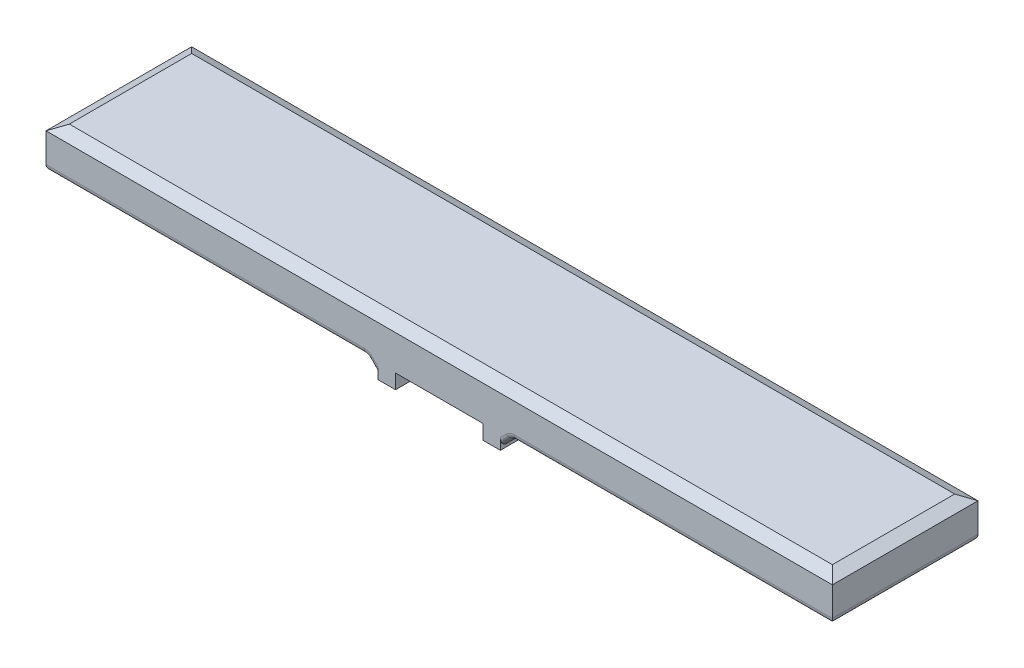
SolidWorks part; units mm, degrees
material "C355.0-T61 Permanent Mold cast (SS)"
ref_plane "Front Plane" through (0, 0, 0) normal (0, 0, 1) x (1, 0, 0)
ref_plane "Top Plane" through (0, 0, 0) normal (0, 1, 0) x (1, 0, 0)
ref_plane "Right Plane" through (0, 0, 0) normal (1, 0, 0) x (0, 0, -1)
sketch "Sketch1" plane through (0, 0, 0) normal (0, 1, 0) x (1, 0, 0)
  line L1 (-675, 125) -> (675, 125)
  line L2 (-675, 125) -> (-675, -125)
  line L3 (-675, -125) -> (675, -125)
  line L4 (675, 125) -> (675, -125)
  line L5 (-675, 125) -> (675, -125) construction
  line L6 (-675, -125) -> (675, 125) construction
  point P0 (0, 0)
  dimension "D1" = 1350
  dimension "D2" = 250
extrude "Boss-Extrude1" add sketch "Sketch1" along normal blind 70 contours L1 L4 L3 L2
chamfer "Chamfer1" distance 10 distance2 20 4 edges at (0, 70, -125) (675, 70, 0) (0, 70, 125) (-675, 70, 0)
sketch "Sketch2" plane through (0, 0, 0) normal (0, -1, 0) x (1, 0, 0)
  line L0 (-75, 125) -> (-75, -125)
  line L1 (-675, 125) -> (675, 125) construction
  line L2 (-675, -125) -> (675, -125) construction
  line L3 (-105, 125) -> (-105, -125)
  line L4 (-105, 125) -> (-75, 125)
  line L5 (-105, -125) -> (-75, -125)
  line L6 (0, 320.5208) -> (0, -388.3091) construction
  line L7 (105, -125) -> (75, -125)
  line L8 (105, 125) -> (75, 125)
  line L9 (105, 125) -> (105, -125)
  line L10 (75, 125) -> (75, -125)
  dimension "D1" = 75
  dimension "D2" = 30
extrude "Boss-Extrude2" add sketch "Sketch2" along normal blind 25
chamfer "Chamfer2" distance 20 angle 45 2 edges at (-105, 0, 0) (105, 0, 0)
fillet "Fillet1" radius 10 12 edges at (115, -10, -125) (115, -10, 125) (-115, -10, 125) (-115, -10, -125) (675, 0, 0) (400, 0, -125) (125, 0, 0) (400, 0, 125) (-675, 0, 0) (-400, 0, 125) (-125, 0, 0) (-400, 0, -125)
sketch "Sketch3" plane through (0, 0, 0) normal (0, -1, 0) x (1, 0, 0)
  circle A0 centre (0, 0) radius 10
  dimension "D1" = 20
extrude "Boss-Extrude3" add sketch "Sketch3" along normal blind 25
chamfer "Chamfer3" distance 3 angle 45 1 edges at (0, -25, -10)
